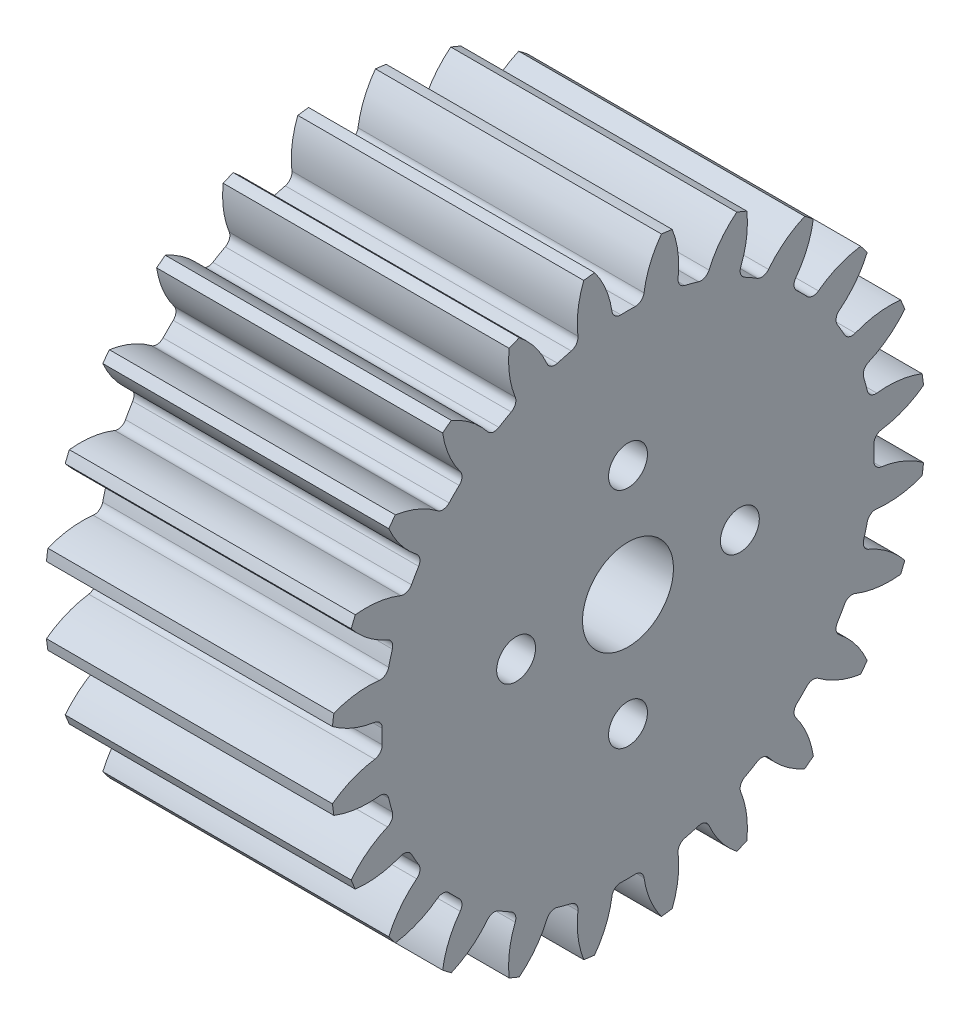
SolidWorks part; units mm, degrees
ref_plane "Front Plane" through (0, 0, 0) normal (0, 0, 1) x (1, 0, 0)
ref_plane "Top Plane" through (0, 0, 0) normal (0, 1, 0) x (1, 0, 0)
ref_plane "Right Plane" through (0, 0, 0) normal (1, 0, 0) x (0, 0, -1)
sketch "Sketch1" plane through (0, 0, 0) normal (1, 0, 0) x (0, 0, -1)
  circle A0 centre (0, 0) radius 3.975
  circle A1 centre (0, 0) radius 26
  dimension "D1" = 7.95
  dimension "D2" = 52
extrude "Boss-Extrude2" add sketch "Sketch1" along normal blind 25
sketch "Sketch3" plane through (25, 0, 0) normal (1, 0, 0) x (0, 0, -1)
  line L0 (0, 0) -> (0, 26) construction
  line L1 (-1.3288, 21.4589) -> (0, 0) construction
  line L2 (0, 18.7925) -> (-1.1272, 21.8894) construction
  circle A0 centre (0, 0) radius 26 construction
  arc A1 (1.3288, 21.4589) -> (-1.3288, 21.4589) centre (0, 0) ccw
  arc A2 (1.8708, 23.927) -> (-1.8708, 23.927) centre (0, 0) ccw construction
  arc A3 (2.9217, 25.8353) -> (-2.9217, 25.8353) centre (0, 0) ccw
  arc A4 (-2.9217, 25.8353) -> (-1.3288, 21.4589) centre (-9.5332, 20.9508) cw
  arc A5 (2.9217, 25.8353) -> (1.3288, 21.4589) centre (9.5332, 20.9508) ccw
  point P17 (-1.8088, 23.7623)
  dimension "D1" = 52
  dimension "D2" = 48
  dimension "D3" = 4.5
  dimension "D4" = 20
  dimension "D5" = 3.7416
extrude "Cut-Extrude1" cut sketch "Sketch3" against normal through all
fillet "Fillet1" radius 0.76 2 edges at (12.5, 21.4589, -1.3288) (12.5, 21.4589, 1.3288)
pattern_circular "CirPattern2" count 24 over 360 about axis through (0, 0, 0) along (1, 0, 0) of "Fillet1", "Cut-Extrude1"
sketch "Sketch4" plane through (25, 0, 0) normal (1, 0, 0) x (0, 0, -1)
  circle A0 centre (0, 0) radius 9.779 construction
  circle A1 centre (0, 9.779) radius 1.7
  circle A2 centre (9.779, 0) radius 1.7
  circle A3 centre (0, -9.779) radius 1.7
  circle A4 centre (-9.779, 0) radius 1.7
  point P5 (0, 0)
  point P6 (8.1512, -2.5081)
  point P7 (0, 0)
  point P14 (0, 0)
  dimension "D1" = 19.558
  dimension "D2" = 3.4
  dimension "D3" = 4
extrude "Cut-Extrude2" cut sketch "Sketch4" against normal blind 10
equation "\"No of teeth\" = 24"
equation "\"Module\"= 2"
equation "\"Outer Diameter\"= ( \"No of teeth\" + 2 ) * \"Module\""
equation "\"Pitch Diameter\"= \"No of teeth\" * \"Module\""
equation "\"Backlash\"= 0.3 * \"Module\""
equation "\"Arc Length\"= ( ( \"Module\" * pi ) / 2 ) + \"Backlash\""
equation "\"Fillet Radius\"= 0.38 * \"Module\""
equation "\"Bore Diameter\"= 7.95"
equation "\"Presseure angle\"= 20"
equation "\"Tooth Depth\"= IIF ( \"Module\" <= 1.25 , 2.4 * \"Module\" , 2.25 * \"Module\" )"
equation "\"D1@Sketch1\"=\"Bore Diameter\""
equation "\"D2@Sketch1\"=\"Outer Diameter\""
equation "\"D1@Sketch3\"=\"Outer Diameter\""
equation "\"D2@Sketch3\"=\"Pitch Diameter\""
equation "\"D3@Sketch3\"=\"Tooth Depth\""
equation "\"D4@Sketch3\"=\"Presseure angle\""
equation "\"D5@Sketch3\"=\"Arc Length\""
equation "\"D1@Fillet1\"=\"Fillet Radius\""
equation "\"D1@CirPattern2\"=\"No of teeth\""
